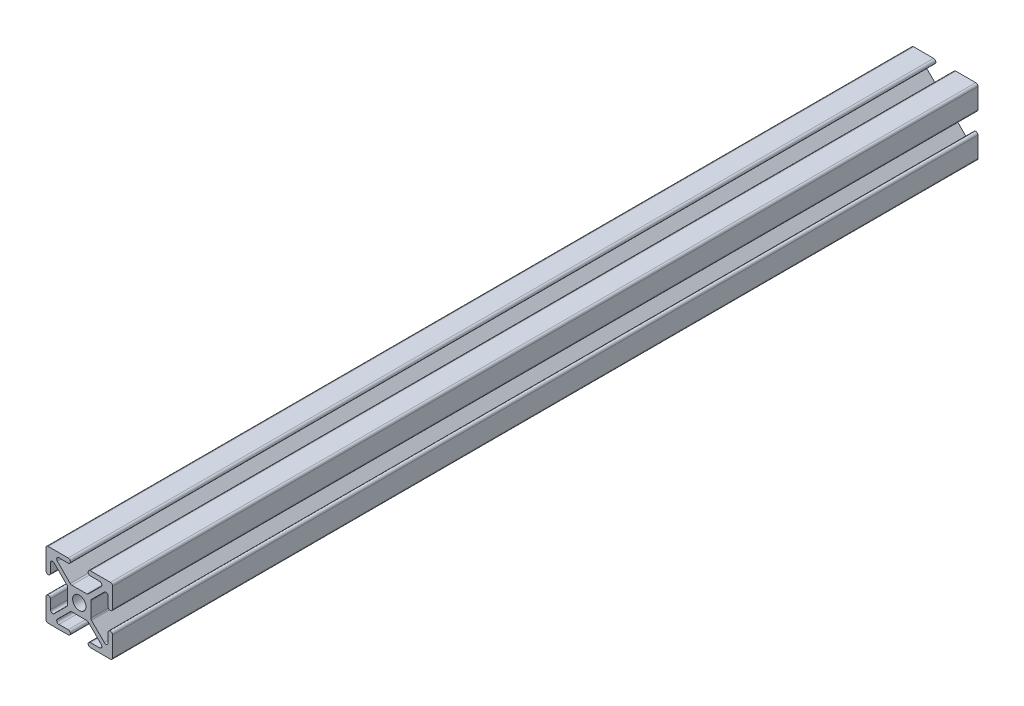
SolidWorks part; units mm, degrees
ref_plane "Alzado" through (0, 0, 0) normal (0, 0, 1) x (1, 0, 0)
ref_plane "Planta" through (0, 0, 0) normal (0, 1, 0) x (1, 0, 0)
ref_plane "Vista lateral" through (0, 0, 0) normal (1, 0, 0) x (0, 0, -1)
sketch "Croquis1" plane through (0, 0, 0) normal (0, 0, 1) x (1, 0, 0)
  line L1 (-14, 15) -> (14, 15)
  line L2 (-15, 14) -> (-15, -14)
  line L3 (-14, -15) -> (14, -15)
  line L4 (15, 14) -> (15, -14)
  line L5 (-15, 15) -> (15, -15) construction
  line L6 (-15, -15) -> (15, 15) construction
  arc A0 (-14, 15) -> (-15, 14) centre (-14, 14) ccw
  arc A1 (14, -15) -> (15, -14) centre (14, -14) ccw
  arc A2 (-14, -15) -> (-15, -14) centre (-14, -14) cw
  arc A3 (15, 14) -> (14, 15) centre (14, 14) ccw
  point P0 (0, 0)
  dimension "D3" = 1
  dimension "D4" = 1
  dimension "D1" = 30
  dimension "D2" = 30
extrude "Saliente-Extruir1" add sketch "Croquis1" against normal blind 390
sketch "Croquis2" plane through (0, 0, 0) normal (0, 0, 1) x (1, 0, 0)
  circle A0 centre (0, 0) radius 3
  dimension "D1" = 6
sketch "Croquis3" plane through (0, 0, 0) normal (0, 0, 1) x (1, 0, 0)
  line L0 (-15, 0) -> (15, 0) construction
  line L1 (4.0787, -5.4929) -> (9.8787, -11.2929)
  line L2 (-11.2929, 9.8787) -> (-5.4929, 4.0787)
  line L3 (-9.8787, 11.2929) -> (-4.0787, 5.4929)
  line L4 (-13, 9.1716) -> (-13, 5)
  line L5 (-15, 14) -> (-15, -14) construction
  line L6 (-5.2, 3.3716) -> (-5.2, -3.3716)
  line L7 (-9.1716, 13) -> (-5, 13)
  line L8 (9.8787, 11.2929) -> (4.0787, 5.4929)
  line L9 (11.2929, 9.8787) -> (5.4929, 4.0787)
  line L10 (-3.3716, 5.2) -> (3.3716, 5.2)
  line L11 (14, 15) -> (-14, 15) construction
  line L12 (13, 9.1716) -> (13, 5)
  line L13 (5.2, 3.3716) -> (5.2, -3.3716)
  line L14 (15, -14) -> (15, 14) construction
  line L15 (-9.1716, -13) -> (-5, -13)
  line L16 (-3.3716, -5.2) -> (3.3716, -5.2)
  line L17 (-14, -15) -> (14, -15) construction
  line L18 (-5.4929, -4.0787) -> (-11.2929, -9.8787)
  line L19 (5.4929, -4.0787) -> (11.2929, -9.8787)
  line L20 (-4.0787, -5.4929) -> (-9.8787, -11.2929)
  line L21 (5, -13) -> (9.1716, -13)
  line L22 (-13, -5) -> (-13, -9.1716)
  line L23 (13, -5) -> (13, -9.1716)
  line L24 (0, 15) -> (0, -5.2) construction
  line L34 (5, 13) -> (9.1716, 13)
  arc A0 (9.8787, 11.2929) -> (9.1716, 13) centre (9.1716, 12) ccw
  arc A1 (-9.8787, 11.2929) -> (-9.1716, 13) centre (-9.1716, 12) cw
  arc A2 (9.8787, 11.2929) -> (9.1716, 13) centre (9.1716, 12) ccw
  arc A3 (13, 9.1716) -> (11.2929, 9.8787) centre (12, 9.1716) ccw
  arc A4 (11.2929, -9.8787) -> (13, -9.1716) centre (12, -9.1716) ccw
  arc A5 (9.1716, -13) -> (9.8787, -11.2929) centre (9.1716, -12) ccw
  arc A6 (-9.1716, -13) -> (-9.8787, -11.2929) centre (-9.1716, -12) cw
  arc A7 (-11.2929, -9.8787) -> (-13, -9.1716) centre (-12, -9.1716) cw
  arc A8 (-13, 9.1716) -> (-11.2929, 9.8787) centre (-12, 9.1716) cw
  arc A9 (-4.0787, -5.4929) -> (-3.3716, -5.2) centre (-3.3716, -6.2) cw
  arc A10 (3.3716, -5.2) -> (4.0787, -5.4929) centre (3.3716, -6.2) cw
  arc A11 (5.4929, -4.0787) -> (5.2, -3.3716) centre (6.2, -3.3716) cw
  arc A12 (5.2, 3.3716) -> (5.4929, 4.0787) centre (6.2, 3.3716) cw
  arc A13 (3.3716, 5.2) -> (4.0787, 5.4929) centre (3.3716, 6.2) ccw
  arc A14 (-3.3716, 5.2) -> (-4.0787, 5.4929) centre (-3.3716, 6.2) cw
  arc A15 (-5.4929, -4.0787) -> (-5.2, -3.3716) centre (-6.2, -3.3716) ccw
  arc A16 (-5.2, 3.3716) -> (-5.4929, 4.0787) centre (-6.2, 3.3716) ccw
  circle A17 centre (-14, -5) radius 1
  circle A18 centre (-14, 5) radius 1
  circle A19 centre (-5, -14) radius 1
  circle A20 centre (5, -14) radius 1
  circle A21 centre (14, 5) radius 1
  circle A22 centre (14, -5) radius 1
  circle A23 centre (-5, 14) radius 1
  circle A24 centre (5, 14) radius 1
  point P20 (-11.5858, -13)
  point P30 (-13, -11.5858)
  point P43 (-3.7858, -5.2)
  point P50 (3.7858, -5.2)
  point P53 (5.2, -3.7858)
  point P62 (-5.2, -3.7858)
  line M2 (-15, 14) -> (-15, -14)
  line M4 (-14, -15) -> (14, -15)
  line M6 (15, -14) -> (15, 14)
  line M8 (14, 15) -> (-14, 15)
  dimension "D6" = 9.8
  dimension "D7" = 2
  dimension "D12" = 2
  dimension "D19" = 1
  dimension "D2" = 1
  dimension "D3" = 1
  dimension "D4" = 1
  dimension "D16" = 1
  dimension "D5" = 2
  dimension "D8" = 9.8
  dimension "D9" = 2
  dimension "D10" = 9.8
  dimension "D11" = 9.8
  dimension "D15" = 1
  dimension "D20" = 1
  dimension "D23" = 1
  dimension "D24" = 1
  dimension "D27" = 1
  dimension "D28" = 1
extrude "Cortar-Extruir1" cut sketch "Croquis2" against normal through all
extrude "Cortar-Extruir3" cut sketch "Croquis3" against normal through all contours A18 A17 L22 A7 L18 A15 L6 A16 L2 A8 L4 M2 | A24 A23 L7 A1 L3 A14 L10 A13 L8 A0 L34 M8 | A20 L21 A5 L1 A10 L16 A9 L20 A6 L15 A19 M4 | A22 A21 L12 A3 L9 A12 L13 A11 L19 A4 L23 M6
